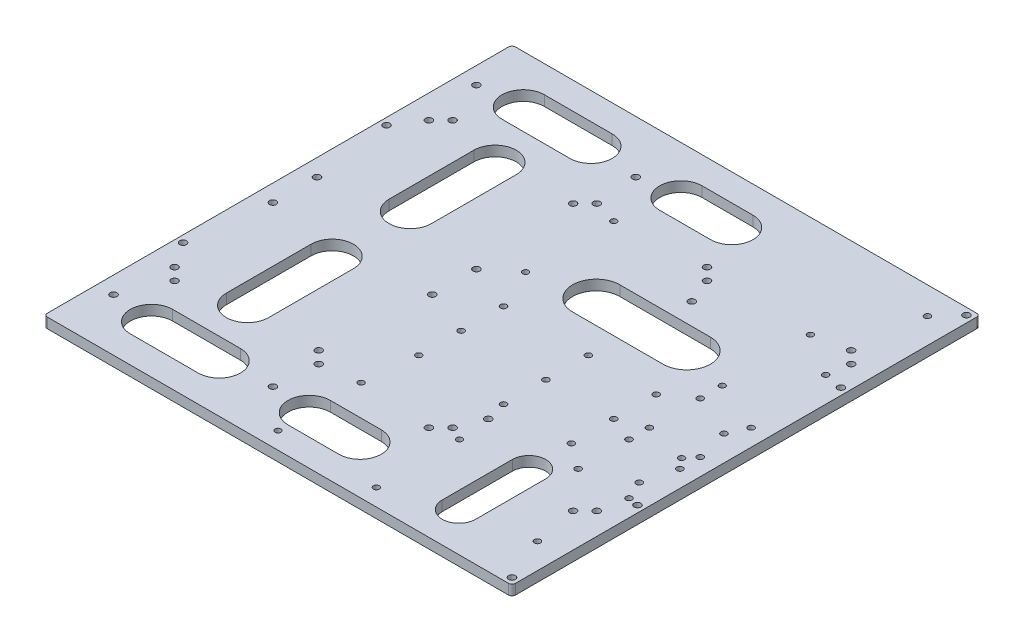
SolidWorks part; units mm, degrees
ref_plane "Спереди" through (0, 0, 0) normal (0, 0, 1) x (1, 0, 0)
ref_plane "Сверху" through (0, 0, 0) normal (0, 1, 0) x (1, 0, 0)
ref_plane "Справа" through (0, 0, 0) normal (1, 0, 0) x (0, 0, -1)
sketch "Эскиз1" plane through (0, 0, 0) normal (0, 1, 0) x (1, 0, 0)
  line L1 (-138, -138) -> (138, -138)
  line L2 (-138, -138) -> (-138, 138)
  line L3 (-138, 138) -> (138, 138)
  line L4 (138, -138) -> (138, 138)
  line L5 (0, 138) -> (0, -138) construction
  line L6 (-138, 0) -> (138, 0) construction
  point P0 (0, 0)
  dimension "D1" = 276
  dimension "D2" = 276
extrude "Бобышка-Вытянуть1" add sketch "Эскиз1" along normal blind 6
fillet "Скругление1" radius 2 4 edges at (138, 3, 138) (-138, 3, 138) (-138, 3, -138) (138, 3, -138)
sketch "Эскиз2" plane through (0, 6, 0) normal (0, 1, 0) x (1, 0, 0)
  line L0 (0, 147.7994) -> (0, 0) construction
  line L1 (0, 0) -> (-164.0684, 0) construction
  line L2 (-164.0684, 0) -> (215.1731, 0) construction
  circle A0 centre (-134, 60) radius 2
  circle A1 centre (134, 60) radius 2
  circle A2 centre (134, -60) radius 2
  circle A3 centre (-134, -60) radius 2
  circle A4 centre (46, 60) radius 2
  circle A5 centre (46, -60) radius 2
  circle A6 centre (134, 134) radius 2
  circle A7 centre (134, -134) radius 2
  point P15 (17.0178, 60)
  point P20 (125.1791, 124.1282)
  dimension "D1" = 134
  dimension "D2" = 60
  dimension "D4" = 134
  dimension "D3" = 46
  dimension "D5" = 134
extrude "Вырез-Вытянуть1" cut sketch "Эскиз2" against normal blind 6
sketch "Эскиз3" plane through (0, 6, 0) normal (0, 1, 0) x (1, 0, 0)
  line L0 (0, 147.4317) -> (0, 0) construction
  line L1 (-193.8488, 0) -> (193.8488, 0) construction
  line L2 (138, -136) -> (138, 136) construction
  line L7 (43, 82) -> (43, -82) construction
  line L13 (43, 75) -> (43, -75) construction
  line L14 (-117, -82) -> (33, -82) construction
  line L16 (-117, 82) -> (33, 82) construction
  line L18 (-42, 82) -> (-42, -82) construction
  line L19 (-89.5005, 0) -> (60.4995, 0) construction
  line L20 (-124, -75) -> (40, -75) construction
  line L22 (-124, 75) -> (40, 75) construction
  line L24 (-42, 75) -> (-42, -75) construction
  line L25 (-96.5005, 0) -> (67.4995, 0) construction
  circle A0 centre (-32, 82) radius 2
  circle A1 centre (118, 82) radius 2
  circle A2 centre (125, 75) radius 2
  circle A3 centre (-39, 75) radius 2
  circle A4 centre (118, -82) radius 2
  circle A5 centre (125, -75) radius 2
  circle A6 centre (-32, -82) radius 2
  circle A7 centre (-39, -75) radius 2
  circle A8 centre (-124, 75) radius 2
  circle A10 centre (40, 75) radius 2
  circle A11 centre (33, 82) radius 2
  circle A12 centre (40, -75) radius 2
  circle A13 centre (33, -82) radius 2
  circle A14 centre (-117, -82) radius 2
  circle A15 centre (-124, -75) radius 2
  circle A16 centre (-117, 82) radius 2
  point P3 (43, 0)
  point P8 (43, 0)
  point P22 (-42, 0)
  point P24 (-42, 0)
  point P33 (-96.5005, 73.8494)
  point P37 (66.3624, 75)
  point P39 (60.4995, 81.8646)
  point P41 (68.5627, -75)
  point P43 (61.4904, -82)
  point P45 (-90.7995, -82)
  point P47 (-97.5574, -75)
  dimension "D3" = 95
  dimension "D1" = 150
  dimension "D2" = 164
  dimension "D4" = 150
  dimension "D5" = 164
  dimension "D6" = 180
extrude "150х164" cut sketch "Эскиз3" against normal blind 6
sketch "Эскиз4" plane through (0, 6, 0) normal (0, 1, 0) x (1, 0, 0)
  line L0 (-244.2183, 0) -> (0, 0) construction
  line L1 (0, 0) -> (0, 146.3288) construction
  line L2 (-177.488, 60) -> (64.2486, 60) construction
  line L3 (-138, 136) -> (-138, -136) construction
  line L4 (-128, 13) -> (-34, 13) construction
  line L5 (-128, 13) -> (-128, 107) construction
  line L6 (-128, 107) -> (-34, 107) construction
  line L7 (-34, 13) -> (-34, 107) construction
  line L8 (-81, 107) -> (-81, 13) construction
  line L9 (-128, 60) -> (-34, 60) construction
  circle A0 centre (-128, 107) radius 2
  circle A1 centre (-34, 107) radius 2
  circle A2 centre (-34, 13) radius 2
  circle A3 centre (-128, 13) radius 2
  circle A4 centre (-128, -13) radius 2
  circle A5 centre (-34, -13) radius 2
  circle A6 centre (-34, -107) radius 2
  circle A7 centre (-128, -107) radius 2
  point P6 (-81, 60)
  dimension "D1" = 94
  dimension "D2" = 94
  dimension "D3" = 60
  dimension "D4" = 10
extrude "94х94" cut sketch "Эскиз4" against normal blind 6
sketch "Эскиз7" plane through (0, 6, 0) normal (0, 1, 0) x (1, 0, 0)
  line L0 (-167.0096, 52) -> (194.2165, 52) construction
  line L2 (-18, 26) -> (98, 26) construction
  line L3 (-18, 26) -> (-18, 78) construction
  line L4 (-18, 78) -> (98, 78) construction
  line L5 (98, 26) -> (98, 78) construction
  line L6 (40, 78) -> (40, 26) construction
  line L7 (-18, 52) -> (98, 52) construction
  line L8 (136, 138) -> (-136, 138) construction
  circle A0 centre (-18, 78) radius 1.75
  circle A1 centre (-18, 26) radius 1.75
  circle A2 centre (98, 78) radius 1.75
  circle A3 centre (98, 26) radius 1.75
  point P2 (40, 52)
  point P11 (-17.6458, 25.6429)
  point P13 (97.4867, 78)
  point P15 (98, 26.5318)
  dimension "D3" = 3.5
  dimension "D1" = 116
  dimension "D2" = 52
  dimension "D4" = 40
  dimension "D5" = 60
extrude "Jetson" cut sketch "Эскиз7" against normal blind 6
sketch "Эскиз8" plane through (0, 6, 0) normal (0, 1, 0) x (1, 0, 0)
  line L0 (-136, -138) -> (136, -138) construction
  line L1 (-10, -128) -> (48, -128) construction
  line L2 (-10, -128) -> (-10, -79) construction
  line L3 (-10, -79) -> (48, -79) construction
  line L4 (48, -128) -> (48, -79) construction
  line L5 (19, -79) -> (19, -128) construction
  line L6 (-10, -103.5) -> (48, -103.5) construction
  line L7 (138, -136) -> (138, 136) construction
  circle A0 centre (48, -79) radius 1.75
  circle A1 centre (-10, -79) radius 1.75
  circle A2 centre (-10, -128) radius 1.75
  circle A3 centre (48, -128) radius 1.75
  point P0 (19, -103.5)
  point P11 (-9.4235, -79)
  point P13 (-9.4966, -128)
  point P15 (48, -128.5017)
  dimension "D5" = 3.5
  dimension "D1" = 58
  dimension "D2" = 49
  dimension "D3" = 10
  dimension "D4" = 90
extrude "Вырез-Вытянуть7" cut sketch "Эскиз8" against normal blind 6
sketch "Эскиз9" plane through (0, 6, 0) normal (0, 1, 0) x (1, 0, 0)
  line L0 (-18.2911, 15.2367) -> (-18.2911, -61.2367) construction
  line L1 (-18.2911, -61.2367) -> (91.6393, -61.2367) construction
  line L2 (91.6393, -61.2367) -> (91.6393, -138) construction
  line L3 (-136, -138) -> (136, -138) construction
  line L4 (91.6393, -138) -> (129.5083, -138) construction
  line L5 (129.5083, -138) -> (129.5083, 138) construction
  line L6 (136, 138) -> (-136, 138) construction
  line L7 (129.5083, 138) -> (112.5959, 138) construction
  line L8 (112.5959, 138) -> (112.5959, 17.8103) construction
  line L9 (112.5959, 17.8103) -> (-18.2911, 17.8103) construction
  line L10 (-18.2911, 17.8103) -> (-18.2911, 15.2367) construction
  line L11 (-18.2911, -23) -> (230.269, -23) construction
  line L12 (138, -136) -> (138, 136) construction
  line L13 (-7, 2) -> (-7, -48) construction
  line L14 (43, 2) -> (43, -48) construction
  line L15 (43, -48) -> (83, -48) construction
  line L16 (83, -48) -> (83, 2) construction
  line L17 (83, 2) -> (123, 2) construction
  line L18 (123, 2) -> (123, -48) construction
  line L19 (98, -17) -> (128, -17) construction
  line L26 (98, -17) -> (98, 13) construction
  line L27 (98, 13) -> (128, 13) construction
  line L28 (128, -17) -> (128, 13) construction
  line L29 (113, 13) -> (113, -17) construction
  line L30 (98, -2) -> (128, -2) construction
  circle A0 centre (-7, 2) radius 1.8
  circle A1 centre (43, 2) radius 1.8
  circle A2 centre (83, 2) radius 1.8
  circle A3 centre (123, 2) radius 1.8
  circle A4 centre (123, -48) radius 1.8
  circle A5 centre (83, -48) radius 1.8
  circle A6 centre (43, -48) radius 1.8
  circle A7 centre (-7, -48) radius 1.8
  circle A8 centre (43, -23) radius 1.8
  circle A9 centre (-7, -23) radius 1.8
  circle A10 centre (83, -23) radius 1.8
  circle A11 centre (123, -23) radius 1.8
  circle A12 centre (123, 62) radius 1.8
  circle A13 centre (123, 122) radius 1.8
  circle A15 centre (123, -108) radius 1.8
  circle A20 centre (98, 13) radius 1.8
  circle A21 centre (128, 13) radius 1.8
  circle A22 centre (98, -17) radius 1.8
  circle A23 centre (128, -17) radius 1.8
  circle A24 centre (98, -29) radius 1.8
  circle A25 centre (128, -29) radius 1.8
  circle A26 centre (128, -59) radius 1.8
  circle A27 centre (98, -59) radius 1.8
  point P48 (265.3099, 17.4821)
  point P56 (235.6358, -12.1897)
  point P58 (265.3099, -11.7745)
  point P61 (113, -2)
  dimension "D1" = 3.6
  dimension "D2" = 50
  dimension "D3" = 40
  dimension "D4" = 40
  dimension "D12" = 30
  dimension "D5" = 25
  dimension "D6" = 60
  dimension "D7" = 60
  dimension "D8" = 115
  dimension "D9" = 15
  dimension "D13" = 30
  dimension "D14" = 10
  dimension "D15" = 140
extrude "Вырез-Вытянуть8" cut sketch "Эскиз9" against normal blind 6
sketch "Эскиз6" plane through (0, 6, 0) normal (0, 1, 0) x (1, 0, 0)
  line L0 (-10, 109.6079) -> (20, 109.6079) construction
  line L1 (-10, 122.1079) -> (20, 122.1079)
  line L2 (-10, 97.1079) -> (20, 97.1079)
  line L3 (0, 56.0682) -> (0, 0) construction
  line L4 (0, 0) -> (164.436, 0) construction
  line L5 (-10, -109.6079) -> (20, -109.6079) construction
  line L6 (-10, -122.1079) -> (20, -122.1079)
  line L7 (-10, -97.1079) -> (20, -97.1079)
  line L8 (5, 131.99) -> (5, -109.6079) construction
  line L9 (-103, 109.6079) -> (-63, 109.6079) construction
  line L10 (-103, 122.1079) -> (-63, 122.1079)
  line L11 (-103, 97.1079) -> (-63, 97.1079)
  line L12 (-138, 136) -> (-138, -136) construction
  line L13 (-103, -109.6079) -> (-63, -109.6079) construction
  line L14 (-103, -122.1079) -> (-63, -122.1079)
  line L15 (-103, -97.1079) -> (-63, -97.1079)
  line L16 (-83, -73) -> (-83, -23) construction
  line L17 (-95.5, -73) -> (-95.5, -23)
  line L18 (-70.5, -73) -> (-70.5, -23)
  line L19 (-136, -138) -> (136, -138) construction
  line L20 (-83, 73) -> (-83, 23) construction
  line L21 (-95.5, 73) -> (-95.5, 23)
  line L22 (-70.5, 73) -> (-70.5, 23)
  line L23 (16.2821, 33.3891) -> (69.672, 33.3891) construction
  line L24 (16.2821, 47.2974) -> (69.672, 47.2974)
  line L25 (16.2821, 19.4808) -> (69.672, 19.4808)
  line L26 (83.6865, -73.6486) -> (83.6865, -114.9629) construction
  line L27 (93.5556, -73.6486) -> (93.5556, -114.9629)
  line L28 (73.8173, -73.6486) -> (73.8173, -114.9629)
  arc A0 (-10, 122.1079) -> (-10, 97.1079) centre (-10, 109.6079) ccw
  arc A1 (20, 97.1079) -> (20, 122.1079) centre (20, 109.6079) ccw
  arc A2 (-10, -122.1079) -> (-10, -97.1079) centre (-10, -109.6079) cw
  arc A3 (20, -97.1079) -> (20, -122.1079) centre (20, -109.6079) cw
  arc A4 (-103, 122.1079) -> (-103, 97.1079) centre (-103, 109.6079) ccw
  arc A5 (-63, 97.1079) -> (-63, 122.1079) centre (-63, 109.6079) ccw
  arc A6 (-103, -122.1079) -> (-103, -97.1079) centre (-103, -109.6079) cw
  arc A7 (-63, -97.1079) -> (-63, -122.1079) centre (-63, -109.6079) cw
  arc A8 (-95.5, -73) -> (-70.5, -73) centre (-83, -73) ccw
  arc A9 (-70.5, -23) -> (-95.5, -23) centre (-83, -23) ccw
  arc A10 (-95.5, 73) -> (-70.5, 73) centre (-83, 73) cw
  arc A11 (-70.5, 23) -> (-95.5, 23) centre (-83, 23) cw
  arc A12 (16.2821, 47.2974) -> (16.2821, 19.4808) centre (16.2821, 33.3891) ccw
  arc A13 (69.672, 19.4808) -> (69.672, 47.2974) centre (69.672, 33.3891) ccw
  arc A14 (93.5556, -73.6486) -> (73.8173, -73.6486) centre (83.6865, -73.6486) ccw
  arc A15 (73.8173, -114.9629) -> (93.5556, -114.9629) centre (83.6865, -114.9629) ccw
  point P2 (5, 109.6079)
  point P13 (5, -109.6079)
  point P22 (-83, 109.6079)
  point P31 (-83, -109.6079)
  point P38 (-83, -48)
  point P47 (-83, 48)
  point P54 (42.977, 33.3891)
  point P61 (83.6865, -94.3058)
  dimension "D1" = 30
  dimension "D2" = 25
  dimension "D3" = 5
  dimension "D4" = 40
  dimension "D5" = 25
  dimension "D6" = 55
  dimension "D7" = 25
  dimension "D8" = 50
  dimension "D9" = 90
extrude "Вырез-Вытянуть5" cut sketch "Эскиз6" against normal blind 6 contours L11 A5 L10 A4 | A11 L22 A10 L21 | L18 A9 L17 A8 | A7 L15 A6 L14 | L25 A13 L24 A12 | L28 A15 L27 A14 | A3 L7 A2 L6 | L2 A1 L1 A0
